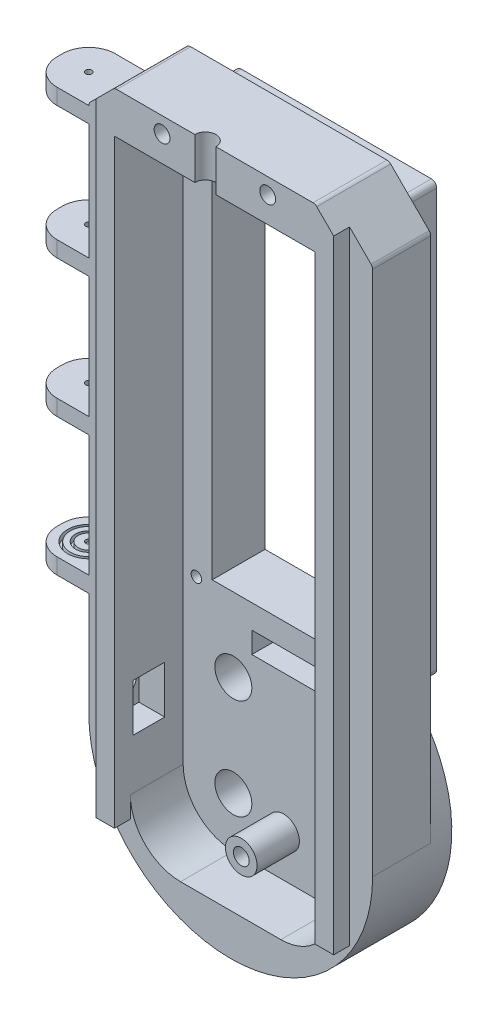
SolidWorks part; units mm, degrees
ref_plane "Alzado" through (0, 0, 0) normal (0, 0, 1) x (1, 0, 0)
ref_plane "Planta" through (0, 0, 0) normal (0, 1, 0) x (1, 0, 0)
ref_plane "Vista lateral" through (0, 0, 0) normal (1, 0, 0) x (0, 0, -1)
sketch "Croquis1" plane through (0, 0, 0) normal (0, 0, 1) x (1, 0, 0)
  line L1 (-19, -40.5) -> (19, -40.5)
  line L2 (-19, -40.5) -> (-19, 40.5)
  line L3 (-19, 40.5) -> (19, 40.5)
  line L4 (19, -40.5) -> (19, 40.5)
  line L5 (-19, -40.5) -> (19, 40.5) construction
  line L6 (-19, 40.5) -> (19, -40.5) construction
  line L7 (-19, -40.5) -> (19, -40.5)
  line L8 (-19, -40.5) -> (-19, -78.5)
  line L9 (-19, -78.5) -> (19, -78.5)
  line L10 (19, -40.5) -> (19, -78.5)
  line L13 (-13.5, 36) -> (13.5, 36)
  line L28 (13.5, 36) -> (13.5, -36)
  line L29 (-13.5, 36) -> (-13.5, -36)
  line L30 (-13.5, -36) -> (13.5, -36)
  circle A0 centre (-9.5, -50) radius 3.5
  circle A1 centre (9.5, -59.5) radius 3.5
  circle A2 centre (-9.5, -69) radius 3.5
  arc A3 (19, -40.5) -> (-19, -40.5) centre (0, -59.5) cw
  point P0 (0, 0)
  point P27 (9.5, -63)
  point P30 (9.5, -54.5)
  point P34 (-13.5, 0)
extrude "Saliente-Extruir1" add sketch "Croquis1" along normal blind 5 contours L1 L4 L3 L2 L30 L29 L13 L28 | L10 L1 L8 L9 A2 A1 A0 | A3 L10 | A3 L9 | A3 L8
sketch "Croquis2" plane through (0, 0, 0) normal (0, 0, -1) x (-1, 0, 0)
  line L0 (-19, 40.5) -> (19, 40.5)
  line L1 (19, -40.5) -> (-19, -40.5)
  line L2 (-19, -40.5) -> (-19, 40.5)
  line L4 (19, -40.5) -> (19, 40.5)
  line L5 (-13.5, 36) -> (-13.5, -36)
  line L7 (-13.5, -36) -> (13.5, -36)
  line L8 (13.5, -36) -> (13.5, 36)
  line L9 (13.5, 36) -> (-13.5, 36)
extrude "Saliente-Extruir2" add sketch "Croquis2" along normal blind 5
sketch "Croquis3" plane through (0, 0, 5) normal (0, 0, 1) x (1, 0, 0)
  line L0 (26.8701, -59.5) -> (26.8701, 40.5)
  line L1 (19, -59.5) -> (19, 40.5)
  line L2 (19, 40.5) -> (-19, 40.5)
  line L3 (-19, 40.5) -> (-19, -59.5)
  line L4 (26.8701, 40.5) -> (19, 48.3701)
  line L5 (19, 48.3701) -> (-19, 48.3701)
  line L6 (-19, 48.3701) -> (-26.8701, 40.5)
  line L7 (-26.8701, 40.5) -> (-26.8701, -59.5)
  arc A2 (-19, -59.5) -> (19, -59.5) centre (0, -59.5) ccw
  arc A3 (-26.8701, -59.5) -> (26.8701, -59.5) centre (0, -59.5) ccw
extrude "Saliente-Extruir9" add sketch "Croquis3" against normal blind 1
sketch "Croquis4" plane through (0, 0, 4) normal (0, 0, -1) x (-1, 0, 0)
  line L0 (-19, 40.5) -> (-19, -40.5)
  line L1 (-19, 40.5) -> (19, 40.5)
  line L2 (19, 40.5) -> (19, -40.5)
  line L3 (14, -77) -> (-14, -77)
  line L4 (-19, -72) -> (-19, -41.338)
  line L5 (19, -72) -> (19, -40.5)
  line L6 (-26.8701, 40.5) -> (-19, 48.3701)
  line L7 (-19, 48.3701) -> (19, 48.3701)
  line L8 (19, 48.3701) -> (26.8701, 40.5)
  line L9 (26.8701, 40.5) -> (26.8701, -59.5)
  line L10 (-26.8701, 40.5) -> (-26.8701, -59.5)
  arc A0 (-19, -40.5) -> (-26.8701, -59.5) centre (0, -59.5) ccw construction
  arc A1 (-14, -77) -> (-19, -72) centre (-14, -72) cw
  arc A2 (14, -77) -> (19, -72) centre (14, -72) ccw
  arc A3 (-19, -40.5) -> (19, -40.5) centre (0, -59.5) ccw construction
  arc A4 (-26.8701, -59.5) -> (26.8701, -59.5) centre (0, -59.5) ccw
  arc M1 (19, -40.5) -> (26.8701, -59.5) centre (0, -59.5) cw
  line M2 (26.8701, -59.5) -> (26.8701, 40.5)
  line M3 (26.8701, 40.5) -> (19, 48.3701)
  line M4 (19, 48.3701) -> (-19, 48.3701)
  line M5 (-19, 48.3701) -> (-26.8701, 40.5)
  line M6 (-26.8701, 40.5) -> (-26.8701, -59.5)
  arc M7 (-26.8701, -59.5) -> (-19, -40.5) centre (0, -59.5) cw
  line M8 (-19, -40.5) -> (-19, 40.5)
  line M9 (-19, 40.5) -> (19, 40.5)
  line M10 (19, 40.5) -> (19, -40.5)
  dimension "D1" = 5
extrude "Saliente-Extruir10" add sketch "Croquis4" against normal blind 11 contours M10 M1 M2 M3 M4 M5 M6 M7 M8 M9
sketch "Croquis5" plane through (0, 0, 5) normal (0, 0, 1) x (1, 0, 0)
  line L0 (-19, -59.5) -> (-19, -69)
  line L1 (19, -69) -> (19, -59.5)
  line L2 (9.5, -78.5) -> (-9.5, -78.5)
  line L3 (19, -59.5) -> (19, -40.5)
  line L4 (-19, -59.5) -> (-19, -40.5)
  arc A0 (-19, -40.5) -> (19, -40.5) centre (0, -59.5) ccw
  arc A1 (-9.5, -78.5) -> (-19, -69) centre (-9.5, -69) cw
  arc A2 (9.5, -78.5) -> (19, -69) centre (9.5, -69) ccw
extrude "Saliente-Extruir11" add sketch "Croquis5" along normal blind 10
fillet "Redondeo1" radius 1 4 edges at (-19, -40.5, -2.5) (-19, 40.5, -0.5) (19, 40.5, -0.5) (19, -40.5, -2.5)
fillet "Redondeo2" radius 1 5 edges at (-18.7071, 40.2071, 4) (18.7071, 40.2071, 4) (-19, -0.5, 4) (0, 40.5, 4) (19, -0.5, 4)
fillet "Redondeo3" radius 1 4 edges at (-26.8701, 40.5, 9.5) (-19, 48.3701, 9.5) (26.8701, 40.5, 9.5) (19, 48.3701, 9.5)
sketch "Croquis6" plane through (-26.8701, 0, 0) normal (-1, 0, 0) x (0, 0, 1)
  line L2 (8.5, -50.5) -> (14.5, -50.5)
  line L3 (14.5, -50.5) -> (14.5, -59.5)
  line L4 (14.5, -59.5) -> (8.5, -59.5)
  line L5 (8.5, -50.5) -> (8.5, -59.5)
extrude "Cortar-Extruir1" cut sketch "Croquis6" against normal blind 8
sketch "Croquis7" plane through (-26.8701, 0, 0) normal (-1, 0, 0) x (0, 0, 1)
  line L0 (8.5, -50.5) -> (14.5, -50.5)
  line L1 (14.5, -50.5) -> (14.5, -59.5)
  line L2 (14.5, -59.5) -> (8.5, -59.5)
  line L3 (8.5, -59.5) -> (8.5, -50.5)
  circle A0 centre (11.5, -55) radius 2.5
extrude "Saliente-Extruir12" add sketch "Croquis7" against normal blind 3
sketch "Croquis8" plane through (-26.8701, 0, 0) normal (-1, 0, 0) x (0, 0, 1)
  line L0 (4, 40.0858) -> (4, 37.0858)
  line L1 (4, 39.5) -> (4, -41.5556) construction
  line L2 (4, 37.0858) -> (15, 37.0858)
  line L3 (15, -59.5) -> (15, 40.0858) construction
  line L4 (15, 37.0858) -> (15, 40.0858)
  line L5 (15, 40.0858) -> (4, 40.0858)
  line L6 (9.5, 37.0858) -> (9.5, 15.0858)
  line L7 (9.5, 15.0858) -> (15, 15.0858)
  line L8 (9.5, 15.0858) -> (4, 15.0858)
  line L9 (4, 15.0858) -> (4, 12.0858)
  line L10 (4, 40.0858) -> (4, -59.5) construction
  line L11 (4, 12.0858) -> (15, 12.0858)
  line L12 (15, 12.0858) -> (15, 15.0858)
  line L13 (9.5, 12.0858) -> (9.5, -10.9142)
  line L14 (9.5, -10.9142) -> (15, -10.9142)
  line L15 (15, -10.9142) -> (15, -13.9142)
  line L16 (15, -13.9142) -> (4, -13.9142)
  line L17 (4, -13.9142) -> (4, -10.9142)
  line L18 (4, -10.9142) -> (9.5, -10.9142)
  line L19 (9.5, -13.9142) -> (9.5, -36.9142)
  line L20 (9.5, -36.9142) -> (15, -36.9142)
  line L21 (15, -36.9142) -> (15, -39.9142)
  line L22 (15, -39.9142) -> (4, -39.9142)
  line L23 (4, -39.9142) -> (4, -36.9142)
  line L24 (4, -36.9142) -> (9.5, -36.9142)
  line M2 (15, -59.5) -> (15, 40.0858)
  line M3 (15, 40.0858) -> (4, 40.0858)
  line M4 (4, 40.0858) -> (4, -59.5)
extrude "Saliente-Extruir13" add sketch "Croquis8" along normal blind 11 contours L2 M4 M2 M3 | L11 L7 L8 M4 M2 | L18 L16 L14 M4 M2 | L24 L22 L20 M4 M2
fillet "Redondeo4" radius 5 8 edges at (-37.8701, -38.4142, 4) (-37.8701, -38.4142, 15) (-37.8701, -12.4142, 4) (-37.8701, -12.4142, 15) (-37.8701, 13.5858, 4) (-37.8701, 13.5858, 15) (-37.8701, 38.5858, 4) (-37.8701, 38.5858, 15)
sketch "Croquis9" plane through (0, 40.0858, 0) normal (0, 1, 0) x (1, 0, 0)
  circle A0 centre (-32.3701, -9.5) radius 0.6
extrude "Cortar-Extruir2" cut sketch "Croquis9" against normal blind 80
sketch "Croquis10" plane through (0, -39.9142, 0) normal (0, -1, 0) x (1, 0, 0)
  circle A0 centre (-32.3701, 9.5) radius 0.6
extrude "Saliente-Extruir14" add sketch "Croquis10" against normal blind 2.5
sketch "Croquis11" plane through (0, -36.9142, 0) normal (0, 1, 0) x (1, 0, 0)
  circle A0 centre (-32.3701, -9.5) radius 2
  circle A1 centre (-32.3701, -9.5) radius 2.5
  circle A2 centre (-32.3701, -9.5) radius 3.5
  circle A3 centre (-32.3701, -9.5) radius 4
extrude "Cortar-Extruir3" cut sketch "Croquis11" against normal blind 1 contours A3 A2 | A1 A0
sketch "Croquis13" plane through (0, 0, 15) normal (0, 0, 1) x (1, 0, 0)
  line L0 (19, 40.5) -> (22.5, 40.5)
  line L1 (19, -69) -> (22.5, -69)
  line L2 (22.5, -69) -> (22.5, 40.5)
  line L3 (19, -69) -> (19, 40.5)
  line L5 (22.5, 40.5) -> (22.5, 44.8701)
  line L6 (-19, -69) -> (-19, 40.5)
  line L7 (-22.5, -69) -> (-22.5, 40.5)
  line L8 (-19, -69) -> (-22.5, -69)
  line L9 (-19, 40.5) -> (-22.5, 40.5)
  line L10 (-19, -69) -> (-19, -65.5)
  line L12 (19, -65.5) -> (19, -69)
  line L13 (-22.5, 40.5) -> (-22.5, 44.8701)
  line L14 (-26.5772, 40.7929) -> (-19.2929, 48.0772) construction
  line L15 (-22.5, 44.8701) -> (-19.2929, 48.0772)
  line L16 (-18.5858, 48.3701) -> (18.5858, 48.3701)
  line L19 (22.5, 44.8701) -> (19.2929, 48.0772)
  arc A0 (-19.2929, 48.0772) -> (-18.5858, 48.3701) centre (-18.5858, 47.3701) cw
  arc A1 (19.2929, 48.0772) -> (18.5858, 48.3701) centre (18.5858, 47.3701) ccw
  line M1 (19, 40.5) -> (19, -69)
  line M5 (-19, -69) -> (-19, 40.5)
  line M6 (-19, 40.5) -> (19, 40.5)
  line M14 (26.5772, 40.7929) -> (19.2929, 48.0772)
  arc M15 (19.2929, 48.0772) -> (18.5858, 48.3701) centre (18.5858, 47.3701) ccw
  line M16 (18.5858, 48.3701) -> (-18.5858, 48.3701)
  arc M17 (-18.5858, 48.3701) -> (-19.2929, 48.0772) centre (-18.5858, 47.3701) ccw
  line M18 (-19.2929, 48.0772) -> (-26.5772, 40.7929)
extrude "Saliente-Extruir15" add sketch "Croquis13" along normal blind 3 contours L6 L9 L7 L8 M5 | L1 L2 L0 L3 M1 | L13 L9 L0 L5 M6 M14 M15 M16 M17 M18
sketch "Croquis14" plane through (0, 0, 4) normal (0, 0, -1) x (-1, 0, 0)
  circle A0 centre (10, 45.3701) radius 1.5
  circle A1 centre (-10, 45.3701) radius 1.5
extrude "Cortar-Extruir4" cut sketch "Croquis14" against normal blind 14
sketch "Croquis16" plane through (0, -69, 0) normal (0, -1, 0) x (-1, 0, 0)
  line L1 (22.5, -15) -> (19, -15)
  line L2 (22.5, -15) -> (22.5, -18)
  line L3 (22.5, -18) -> (19, -18)
  line L4 (-19, -15) -> (-22.5, -15)
  line L5 (-19, -15) -> (-19, -18)
  line L6 (-19, -18) -> (-22.5, -18)
  line L7 (-22.5, -15) -> (-22.5, -18)
  line L8 (19, -15) -> (19, -18)
extrude "Saliente-Extruir16" add sketch "Croquis16" along normal blind 4
sketch "Croquis25" plane through (0, 0, 18) normal (0, 0, 1) x (1, 0, 0)
  line L0 (-10, 45.3701) -> (10, 45.3701)
  line L1 (0, 45.3701) -> (0, -70.6299)
  circle A0 centre (0, -70.6299) radius 3
  circle A1 centre (0, -70.6299) radius 1.5
extrude "Saliente-Extruir21" add sketch "Croquis25" against normal blind 18
sketch "Croquis26" plane through (0, 0, 18) normal (0, 0, 1) x (1, 0, 0)
  circle A0 centre (0, -70.6299) radius 1.5
extrude "Cortar-Extruir7" cut sketch "Croquis26" against normal blind 18
sketch "Croquis28" plane through (0, 0, 5) normal (0, 0, 1) x (1, 0, 0)
  circle A0 centre (-16.5, 38) radius 1
  circle A1 centre (14.5, 38) radius 1
  circle A2 centre (14.5, -37) radius 1
  circle A3 centre (-16.5, -37) radius 1
extrude "Cortar-Extruir8" cut sketch "Croquis28" against normal blind 4
sketch "Croquis29" plane through (0, 0, 18) normal (0, 0, 1) x (1, 0, 0)
  circle A0 centre (0, -70.6299) radius 1.5
  circle A1 centre (0, -70.6299) radius 3
extrude "Cortar-Extruir9" cut sketch "Croquis29" against normal blind 5
sketch "Croquis30" plane through (0, 0, 18) normal (0, 0, 1) x (1, 0, 0)
  line L3 (-1.8, 45.3701) -> (-1.8, 40.5)
  line L5 (-19, 40.5) -> (19, 40.5) construction
  line L6 (-1.8, 40.5) -> (0.2, 40.5)
  line L8 (0.2, 40.5) -> (0.2, 48.3701)
  line L9 (18.5858, 48.3701) -> (-18.5858, 48.3701) construction
  line L10 (0.2, 48.3701) -> (-1.8, 48.3701)
  line L11 (-1.8, 48.3701) -> (-1.8, 45.3701)
revolve "Cortar-Revolución1" cut sketch "Croquis30" angle 360 about L3
sketch "Croquis31" plane through (0, 0, 5) normal (0, 0, 1) x (1, 0, 0)
  line L3 (-6, -40.5) -> (-6, -44.5)
  line L4 (-6, -44.5) -> (10, -44.5)
  line L5 (10, -44.5) -> (10, -40.5)
  line L6 (10, -40.5) -> (-6, -40.5)
extrude "Cortar-Extruir10" cut sketch "Croquis31" against normal up to surface (5 mm away) up to face at (1.5, -70.6299, 0)
